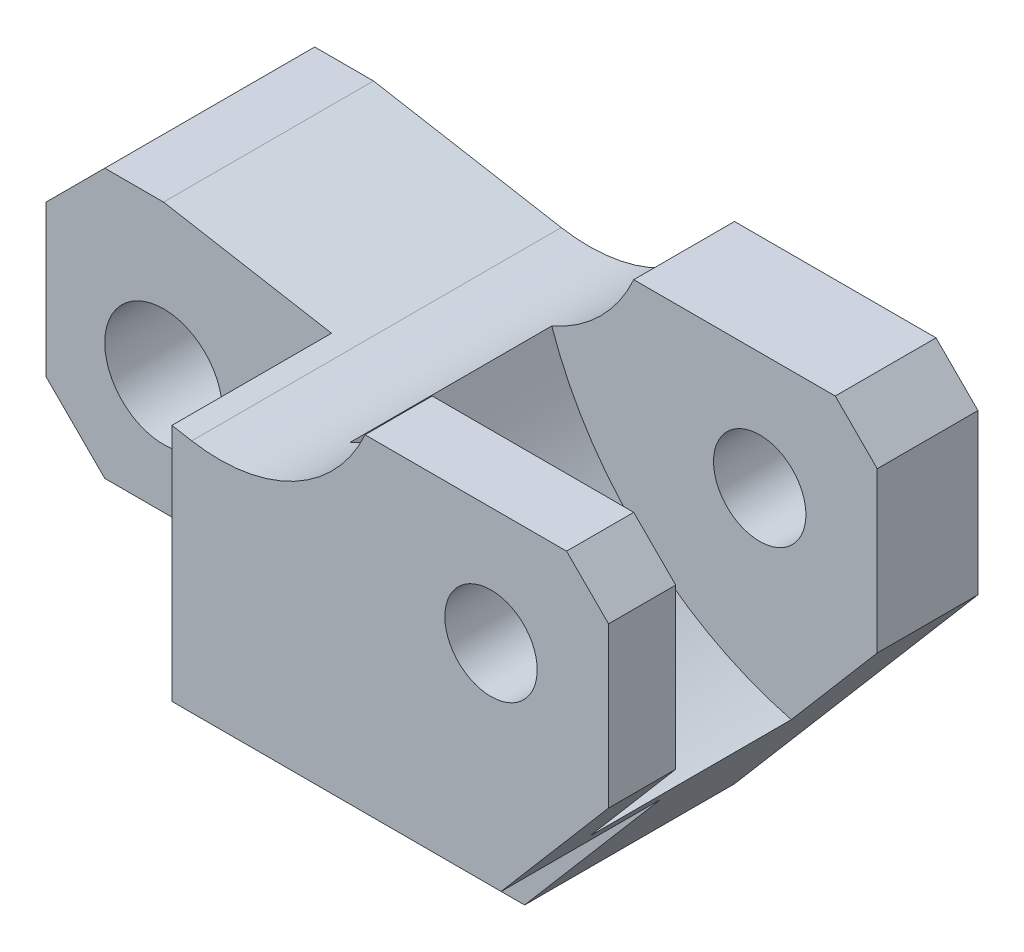
SolidWorks part; units mm, degrees
material "AISI 1020"
ref_plane "Plan de face" through (0, 0, 0) normal (0, 0, 1) x (1, 0, 0)
ref_plane "Plan de dessus" through (0, 0, 0) normal (0, 1, 0) x (1, 0, 0)
ref_plane "Plan de droite" through (0, 0, 0) normal (1, 0, 0) x (0, 0, -1)
sketch "Esquisse1" plane through (0, 0, 0) normal (0, 0, 1) x (1, 0, 0)
  line L0 (-14, 18) -> (0, 18)
  line L1 (72, -33) -> (-14, -33) construction
  line L2 (72, -33) -> (72, 25) construction
  line L3 (72, 25) -> (-14, 25) construction
  line L4 (-14, -33) -> (-14, 25) construction
  line L5 (0, 18) -> (22.3614, 14.0571)
  line L6 (43, 25) -> (67, 25)
  line L7 (67, 25) -> (72, 25)
  line L8 (72, 25) -> (72, 1)
  line L9 (72, 1) -> (43, -33)
  line L10 (43, -33) -> (37.297, -33)
  line L12 (25.5755, -14) -> (-14, -14)
  line L13 (-14, -14) -> (-14, 18)
  circle A0 centre (0, 0) radius 7
  arc A1 (22.3614, 14.0571) -> (43, 25) centre (25.6607, 32.7684) ccw
  arc A2 (37.297, -33) -> (30.5212, -18.2647) centre (59.2059, -14) cw
  arc A3 (30.5212, -18.2647) -> (25.5755, -14) centre (25.5755, -19) ccw
  circle A4 centre (58, 11) radius 5.5
  dimension "D13" = 5
  dimension "D14" = 29
  dimension "D9" = 19
  dimension "D18" = 14
  dimension "D1" = 86
  dimension "D2" = 58
  dimension "D4" = 24
  dimension "D5" = 14
  dimension "D6" = 14
  dimension "D7" = 32
  dimension "D8" = 19
  dimension "D12" = 10
  dimension "D15" = 29
  dimension "D16" = 14
  dimension "D17" = 19
  dimension "D3" = 29
  dimension "D10" = 14
  dimension "D11" = 14
extrude "Boss.-Extru.1" add sketch "Esquisse1" along normal blind 44
chamfer "Chanfrein1" distance 7 angle 45 2 edges at (-14, -14, 22) (-14, 18, 22)
chamfer "Chanfrein2" distance 5 angle 45 1 edges at (72, 25, 22)
sketch "Esquisse2" plane through (0, 25, 0) normal (0, 1, 0) x (1, 0, 0)
  line L0 (-14, -44) -> (-14, -25)
  line L1 (-14, -44) -> (-14, 0) construction
  line L2 (-14, -25) -> (20, -25)
  line L3 (20, -25) -> (20, -44)
  line L4 (22.3614, -44) -> (0, -44) construction
  line L5 (-14, -44) -> (20, -44)
  dimension "D1" = 19
  dimension "D2" = 34
extrude "Enlèv. mat.-Extru.1" cut sketch "Esquisse2" against normal through all
sketch "Esquisse4" plane through (72, 0, 0) normal (1, 0, 0) x (0, 0, -1)
  line L1 (-44, -33) -> (-25, -33)
  line L2 (-44, -33) -> (-44, -14)
  line L3 (-44, -14) -> (-25, -14)
  line L4 (-25, -33) -> (-25, -14)
  dimension "D1" = 19
  dimension "D2" = 19
extrude "Enlèv. mat.-Extru.2" cut sketch "Esquisse4" against normal through all contours L2 L1 L4 L3
sketch "Esquisse5" plane through (0, 0, 0) normal (0, 0, -1) x (-1, 0, 0)
  line L11 (-43, 25) -> (-67, 25)
  line L12 (-67, 25) -> (-72, 20)
  line L13 (-72, 20) -> (-72, 1)
  line L14 (-72, 1) -> (-43, -33)
  line L15 (-43, -33) -> (-37.297, -33)
  line L16 (-25.5755, -14) -> (7, -14)
  line L17 (7, -14) -> (14, -7)
  line L18 (14, -7) -> (14, 11)
  line L19 (14, 11) -> (7, 18)
  line L20 (7, 18) -> (0, 18)
  line L21 (0, 18) -> (-22.3614, 14.0571)
  line L22 (-43, 25) -> (-67, 25)
  line L23 (-67, 25) -> (-72, 20)
  line L24 (-72, 20) -> (-72, 1)
  line L25 (-72, 1) -> (-61.7647, -11)
  arc A0 (-61.7647, -11) -> (-33.2369, 15.3443) centre (-72, 28.7019) ccw
  arc A4 (-37.297, -33) -> (-30.5212, -18.2647) centre (-59.2059, -14) ccw
  arc A5 (-25.5755, -14) -> (-30.5212, -18.2647) centre (-25.5755, -19) ccw
  arc A6 (-43, 25) -> (-22.3614, 14.0571) centre (-25.6607, 32.7684) ccw
  arc A9 (-43, 25) -> (-33.2369, 15.3443) centre (-25.6607, 32.7684) ccw
  dimension "D2" = 41
  dimension "D3" = 36
  dimension "D1" = 0
extrude "Enlèv. mat.-Extru.3" cut sketch "Esquisse5" against normal blind 24 from offset 12 contours L22 L23 L24 L25 A0 A9
equation "\"A\" = 86"
equation "\"B\" = 58"
equation "\"C\"= 44"
equation "\"D1@Boss.-Extru.1\"=\"C\""
equation "\"D1@Esquisse1\"=\"A\""
equation "\"D2@Esquisse1\"=\"B\""
equation "\"D2@Esquisse2\"=\"A\" - 52"
